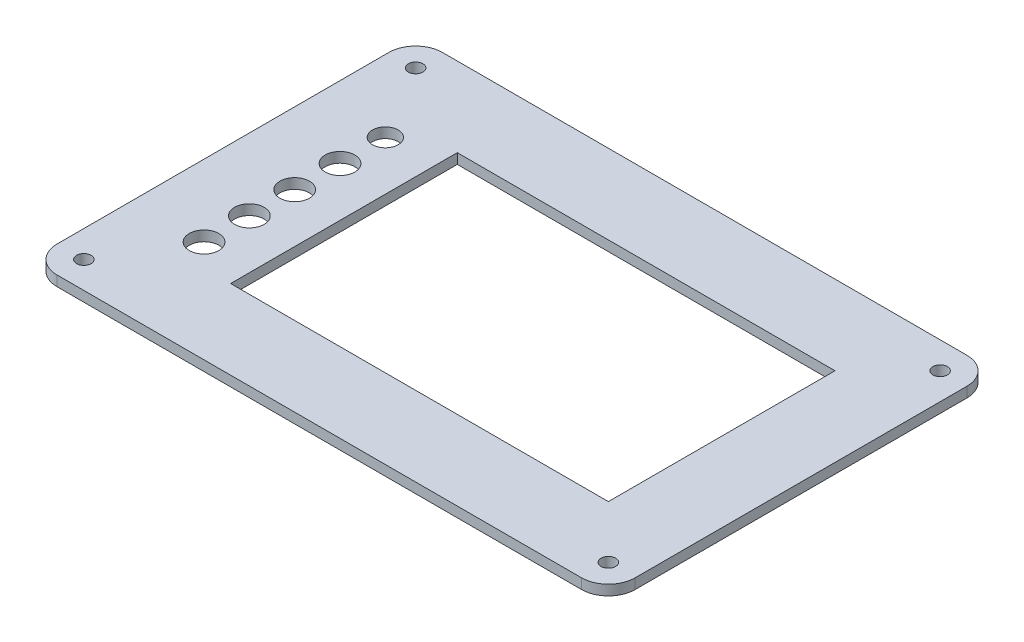
SolidWorks part; units mm, degrees
material "Plain Carbon Steel"
ref_plane "Front" through (0, 0, 0) normal (0, 0, 1) x (1, 0, 0)
ref_plane "Top" through (0, 0, 0) normal (0, 1, 0) x (1, 0, 0)
ref_plane "Right" through (0, 0, 0) normal (1, 0, 0) x (0, 0, -1)
sketch "Sketch1" plane through (0, 0, 0) normal (0, 1, 0) x (1, 0, 0)
  line L0 (-45, 0) -> (45, 0) construction
  line L1 (-45, 30) -> (45, 30) construction
  line L2 (-45, 30) -> (-45, -30) construction
  line L3 (-45, -30) -> (45, -30) construction
  line L4 (45, 30) -> (45, -30) construction
  line L5 (0, -30) -> (0, 30) construction
  line L6 (41.825, 26.825) -> (41.825, -26.825) construction
  line L7 (-41.825, -26.825) -> (41.825, -26.825) construction
  line L8 (-41.825, 26.825) -> (-41.825, -26.825) construction
  line L9 (-41.825, 26.825) -> (41.825, 26.825) construction
  line L10 (40.825, 25.825) -> (40.825, -25.825) construction
  line L11 (-40.825, -25.825) -> (40.825, -25.825) construction
  line L12 (-40.825, 25.825) -> (-40.825, -25.825) construction
  line L13 (-40.825, 25.825) -> (40.825, 25.825) construction
  line L14 (40.825, 21.65) -> (45, 21.65) construction
  line L15 (40.825, -21.65) -> (45, -21.65) construction
  line L16 (36.65, -25.825) -> (36.65, -30) construction
  line L17 (-36.65, -25.825) -> (-36.65, -30) construction
  line L18 (-40.825, -21.65) -> (-45, -21.65) construction
  line L19 (-36.65, 25.825) -> (-36.65, 30) construction
  line L20 (-40.825, 21.65) -> (-45, 21.65) construction
  line L21 (36.65, 25.825) -> (36.65, 30) construction
  line L22 (40.825, -25.825) -> (41.825, -25.825) construction
  circle A0 centre (-40.825, -25.825) radius 1 construction
  circle A1 centre (40.825, -25.825) radius 1 construction
  circle A2 centre (40.825, 25.825) radius 1 construction
  circle A3 centre (-40.825, 25.825) radius 1 construction
  circle A4 centre (40.825, -25.825) radius 4.175 construction
  circle A5 centre (40.825, 25.825) radius 4.175 construction
  circle A6 centre (-40.825, 25.825) radius 4.175 construction
  circle A7 centre (-40.825, -25.825) radius 4.175 construction
  dimension "D1" = 90
  dimension "D2" = 60
  dimension "D4" = 1
  dimension "D3" = 3.175
sketch "Sketch2" plane through (0, 0, 0) normal (0, 1, 0) x (1, 0, 0)
  line L0 (-45, 30) -> (-45, -30) construction
  line L1 (-45, -30) -> (45, -30) construction
  line L2 (45, 30) -> (45, -30) construction
  line L3 (-45, 30) -> (45, 30) construction
  line L16 (-45, 25.825) -> (-45, -25.825)
  line L17 (-40.825, -30) -> (40.825, -30)
  line L18 (45, 25.825) -> (45, -25.825)
  line L19 (-40.825, 30) -> (40.825, 30)
  circle A0 centre (40.825, 25.825) radius 4.175 construction
  circle A2 centre (-40.825, 25.825) radius 4.175 construction
  circle A4 centre (40.825, 25.825) radius 1.1303
  circle A5 centre (40.825, -25.825) radius 1.1303
  arc A6 (45, 25.825) -> (40.825, 30) centre (40.825, 25.825) ccw
  circle A7 centre (-40.825, 25.825) radius 1.1303
  arc A8 (-40.825, 30) -> (-45, 25.825) centre (-40.825, 25.825) ccw
  circle A9 centre (-40.825, -25.825) radius 1.1303
  arc A17 (-45, -25.825) -> (-40.825, -30) centre (-40.825, -25.825) ccw
  arc A18 (40.825, -30) -> (45, -25.825) centre (40.825, -25.825) ccw
  dimension "D1" = 2.2606
  dimension "D2" = 2.2606
  dimension "D3" = 2.2606
  dimension "D4" = 2.2606
extrude "Boss-Extrude3" add sketch "Sketch2" along normal blind 1.5875
sketch "Sketch3" plane through (0, 1.5875, 0) normal (0, 1, 0) x (1, 0, 0)
  line L0 (45, 0) -> (-45, 0) construction
  line L1 (-26.16, 17.64) -> (32.64, 17.64)
  line L2 (-26.16, 17.64) -> (-26.16, -17.64)
  line L3 (-26.16, -17.64) -> (32.64, -17.64)
  line L4 (32.64, 17.64) -> (32.64, -17.64)
  line L5 (-26.16, 17.64) -> (32.64, -17.64) construction
  line L6 (-26.16, -17.64) -> (32.64, 17.64) construction
  line L7 (45, -25.825) -> (45, 25.825) construction
  line L8 (-45, 25.825) -> (-45, -25.825) construction
  point P0 (3.24, 0)
  dimension "D1" = 58.8
  dimension "D2" = 35.28
  dimension "D3" = 12.36
sketch "Sketch4" plane through (0, 1.5875, 0) normal (0, 1, 0) x (1, 0, 0)
  line L0 (-33.825, 14.109) -> (-33.825, -14.115) construction
  line L1 (-33.825, -14.115) -> (-45, -14.115) construction
  line L2 (-45, 25.825) -> (-45, -25.825) construction
  circle A10 centre (-33.825, 14.109) radius 1.9986
  circle A11 centre (-33.825, 7.053) radius 2.3
  circle A12 centre (-33.825, -0.003) radius 2.3
  circle A13 centre (-33.825, -7.059) radius 2.3
  circle A14 centre (-33.825, -14.115) radius 2.3
  dimension "D3" = 4.6
  dimension "D4" = 4.6
  dimension "D5" = 4.6
  dimension "D6" = 4.6
  dimension "D7" = 7.056
  dimension "D1" = 3.9972
  dimension "D2" = 11.175
  dimension "D8" = 7.056
  dimension "D9" = 7.056
  dimension "D10" = 7.056
extrude "Cut-Extrude1" cut sketch "Sketch4" against normal through all
extrude "Cut-Extrude2" cut sketch "Sketch3" against normal through all
sketch "Sketch5" plane through (0, 1.5875, 0) normal (0, 1, 0) x (1, 0, 0)
  line L0 (3.24, 17.64) -> (3.24, -17.64) construction
  line L1 (32.64, 17.64) -> (-26.16, 17.64) construction
  line L2 (-26.16, -17.64) -> (32.64, -17.64) construction
  line L3 (32.64, 0) -> (-26.16, 0) construction
  line L4 (32.64, -17.64) -> (32.64, 17.64) construction
  line L5 (-26.16, 17.64) -> (-26.16, -17.64) construction
hole_wizard "Tap Drill for #4-40 Tap1" positions "3DSketch1" profile "Sketch6" hole size "#4-40" standard "ANSI Inch" end condition through all
sketch3d "3DSketch1"
  line L0 (-40.825, 1.5875, 25.825) -> (-40.825, 0, 25.825) construction
  line L1 (-40.825, 1.5875, -25.825) -> (-40.825, 0, -25.825) construction
  line L2 (40.825, 1.5875, -25.825) -> (40.825, 0, -25.825) construction
  line L3 (40.825, 1.5875, 25.825) -> (40.825, 0, 25.825) construction
  point P0 (-40.825, 1.5875, 25.825)
  point P5 (-40.825, 1.5875, -25.825)
  point P10 (40.825, 1.5875, -25.825)
  point P15 (40.825, 1.5875, 25.825)
sketch "Sketch6" plane through (-40.825, 1.5875, 25.825) normal (1, 0, 0) x (0, 0, 1)
  line L0 (0, 0) -> (0, 1.5875)
  line L1 (0, 1.5875) -> (1.1303, 1.5875)
  line L2 (1.1303, 1.5875) -> (1.1303, 0)
  line L5 (1.1303, 0) -> (0, 0)
  line L11 (0, -6.35) -> (0, 107.95) construction
  dimension "Thru Hole Dia." = 2.2606
  dimension "Thru Hole Depth" = 1.5875
